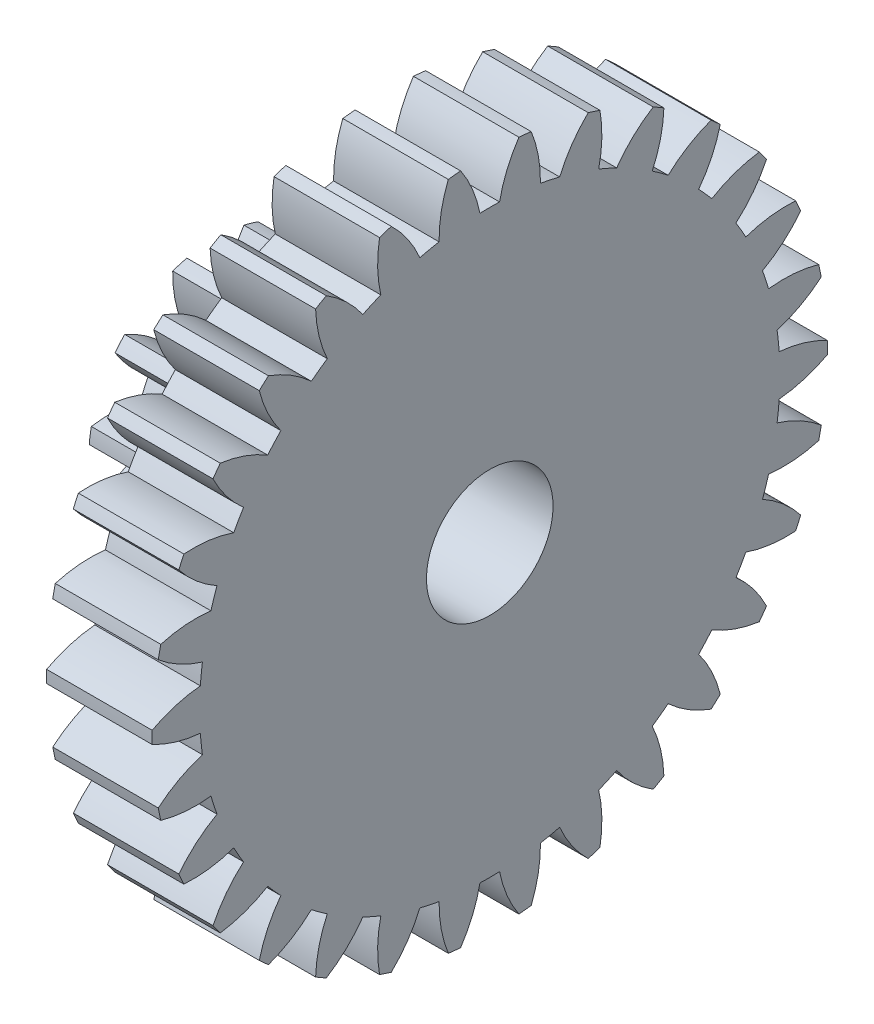
SolidWorks part; units mm, degrees
ref_plane "Plane1" through (0, 0, 0) normal (0, 0, 1) x (1, 0, 0)
ref_plane "Plane2" through (0, 0, 0) normal (0, 1, 0) x (1, 0, 0)
ref_plane "Plane3" through (0, 0, 0) normal (1, 0, 0) x (0, 0, -1)
sketch "HoldingSke" plane through (0, 0, 0) normal (0, 1, 0) x (1, 0, 0)
  line L0 (0, 0) -> (1.7321, -1)
  line L1 (-15, 0) -> (100, 0) construction
  line L2 (0, 0) -> (-2.1039, 2.3779)
  line L3 (0, 0) -> (-11.863, 4.5341)
  line L4 (0, 0) -> (7.479, 4.318)
  line L5 (0, 0) -> (-6.0902, -2.2715)
  line L6 (0, 0) -> (-2.0724, -1.3983)
  line L7 (-2.1039, 2.3779) -> (-0.7048, 8.7256)
  line L8 (-76.2, 54.61) -> (-75.7, 54.61)
  line L9 (-71.009, 38.7566) -> (-53.1078, 45.2721)
  line L10 (-76.2, 71.12) -> (104.1128, 71.12)
  line L11 (0, 0) -> (-2.5, 0)
  line L12 (-76.2, 101.6) -> (-76.181, 101.6)
  line L13 (24.9733, 27.94) -> (52.9518, 28.4284)
  line L14 (24.9733, 27.94) -> (24.9743, 27.94)
  line L15 (24.9733, 27.94) -> (100.4006, 29.5858)
  line L16 (-63.627, -0.5) -> (-12.827, -0.5)
  circle A0 centre (0, 0) radius 1.5
  circle A1 centre (0, 0) radius 3
  circle A2 centre (0, 0) radius 3
  circle A3 centre (0, 0) radius 1.5
  dimension "MHD" = 6
  dimension "Hub_dia" = 6
  dimension "Bore" = 3
  dimension "MBD" = 3
  dimension "Num_teeth" = 30
  dimension "Pitch" = 2
  dimension "Overall_len" = 6.5
  dimension "Show_teeth" = 30
  dimension "Thickness" = 2.5
  dimension "OAL" = 6.5001
  dimension "T_dim" = 0.5
  dimension "Ap" = 20
  dimension "H" = 19.05
  dimension "Pitch_radius" = 180.3128
  dimension "Width" = 2.5
  dimension "Backlash" = 0.019
  dimension "Addendum_fac" = 1
  dimension "Dedendum_fac" = 1.25
  dimension "Clearance_fac" = 0.25
  dimension "Dedendum_add" = 0.001
  dimension "Module" = 0.5
sketch "BasProSke" plane through (0, 0, 0) normal (0, 1, 0) x (1, 0, 0)
  line L0 (-10, 0) -> (60, 0) construction
  line L1 (0, 0) -> (0, 8)
  line L2 (0, 0) -> (2.5, 0)
  line L3 (2.5, 0) -> (2.5, 8)
  line L4 (2.5, 8) -> (0, 8)
  dimension "Thickness" = 2.5
  dimension "Diameter" = 16
revolve "Base-Revolve" add sketch "BasProSke" angle 360 about L0
sketch "TooCutSke" plane through (0, 0, 0) normal (1, 0, 0) x (0, 0, -1)
  line L1 (0, 0) -> (0, 107) construction
  line L2 (0, 0) -> (-0.4258, 7.4879) construction
  line L3 (0, 0) -> (-1.5661, 14.9007) construction
  line L4 (-0.4258, 7.4879) -> (-0.7831, 7.4504) construction
  arc A0 (0.2331, 6.87) -> (-0.2331, 6.87) centre (0, 0) ccw
  arc A1 (0.707, 7.9942) -> (-0.707, 7.9942) centre (0, 0) ccw
  circle A2 centre (0, 0) radius 7.5 construction
  circle A3 centre (0, 0) radius 7.0477 construction
  arc A4 (-0.2331, 6.87) -> (-0.707, 7.9942) centre (-3.1767, 6.2911) ccw
  arc A5 (0.707, 7.9942) -> (0.2331, 6.87) centre (3.1767, 6.2911) ccw
  dimension "Root_dia" = 13.748
  dimension "Overcut_dia" = 16.0508
  dimension "Pitch_dia" = 15
  dimension "Base_dia" = 14.0954
  dimension "Flank_rad" = 3
  dimension "Half_ang" = 6
  dimension "Half_CT" = 0.3593
extrude "ToothCut" cut sketch "TooCutSke" along normal through all
fillet "Breaks" [suppressed] radius 0.01
fillet "RootFillets" [suppressed] radius 0.126
pattern_circular "TeethCuts" count 30 over 360 about axis through (0, 0, 0) along (1, 0, 0) of "ToothCut", "RootFillets", "Breaks"
sketch "HubNeaOneSke" plane through (0, 0, 0) normal (-1, 0, 0) x (0, 0, 1)
  circle A0 centre (0, 0) radius 3
  dimension "Diameter" = 6
extrude "HubNearOne" add sketch "HubNeaOneSke" along normal blind 4.0001
sketch "HubNeaBotSke" plane through (0, 0, 0) normal (-1, 0, 0) x (0, 0, 1)
  circle A0 centre (0, 0) radius 3
  dimension "Diameter" = 6
extrude "HubNearBoth" [suppressed] add sketch "HubNeaBotSke" along normal blind 2
ref_plane "FarPln" through (2.5, 0, 0) normal (1, 0, 0) x (0, 0, -1)
sketch "HubFarSke" plane through (2.5, 0, 0) normal (1, 0, 0) x (0, 0, -1)
  circle A0 centre (0, 0) radius 3
  dimension "Diameter" = 6
extrude "HubFar" [suppressed] add sketch "HubFarSke" along normal blind 2
sketch "BorSke" plane through (0, 0, 0) normal (1, 0, 0) x (0, 0, -1)
  circle A0 centre (0, 0) radius 1.5
  dimension "Diameter" = 3
extrude "Bore" cut sketch "BorSke" along normal mid plane 13.0001
sketch "KeySke" plane through (0, 0, 0) normal (1, 0, 0) x (0, 0, -1)
  line L0 (-0.6, 0) -> (-0.6, 2)
  line L1 (-0.6, 2) -> (0.6, 2)
  line L2 (0.6, 2) -> (0.6, 0)
  line L3 (0, 0) -> (0, 34) construction
  line L4 (-0.6, 0) -> (0.6, 0)
  dimension "Offset" = 2
  dimension "Width" = 1.2
extrude "Keyway" [suppressed] cut sketch "KeySke" along normal mid plane 13.0001
pattern_circular "Keyway2" [suppressed] count 2 every 90 about axis through (-10, 0, 0) along (1, 0, 0)
sketch "Sketch2" plane through (-4.0001, 0, 0) normal (-1, 0, 0) x (0, 0, 1)
  line L0 (0, 1.8486) -> (0, 3) construction
  line L1 (0, 1.8486) -> (0, 0) construction
  arc A0 (0.2331, 1.8446) -> (-0.2331, 1.8446) centre (0, -5.0254) ccw
  arc A1 (0.707, 2.9688) -> (-0.707, 2.9688) centre (0, -5.0254) ccw
  arc A2 (-0.2331, 1.8446) -> (-0.707, 2.9688) centre (-3.1767, 1.2657) ccw
  circle A5 centre (0, 0) radius 3 construction
  arc A6 (0.2331, 1.8446) -> (0.707, 2.9688) centre (3.1767, 1.2657) cw
  point P8 (0, 0)
  dimension "D1" = 8.0254
  dimension "D4" = 3
  dimension "D2" = 1.1514
  dimension "D5" = 0.4662
  dimension "D6" = 0.707
extrude "Cut-Extrude1" cut sketch "Sketch2" against normal up to surface (4.0001 mm away) up to face at (0, 0, -3)
pattern_circular "CirPattern1" count 11 over 360 about axis through (0, 0, 0) along (1, 0, 0) of "Cut-Extrude1"
equation "' \"Module@HoldingSke\" = 6.35"
equation "' \"Num_teeth@HoldingSke\" = 12"
equation "' \"Ap@HoldingSke\" =  20"
equation "' \"Ap@HoldingSke\" = 20"
equation "' \"Width@HoldingSke\" = 0.5 * 25.4"
equation "' \"Hub_dia@HoldingSke\"= 1 * 25.4"
equation "' \"Hub_dia@HoldingSke\" = 1 * 25.4"
equation "' \"Overall_len@HoldingSke\" = 1.0 * 25.4"
equation "' \"Bore@HoldingSke\" = 0.75 * 25.4"
equation "' \"T_dim@HoldingSke\" = 0.1 * 25.4"
equation "' \"Width@KeySke\" = 0.25 * 25.4"
equation "' \"Show_teeth@HoldingSke\" = 13"
equation "' \"Backlash@HoldingSke\" = 0.009 * 25.4"
equation "' \"Addendum_fac@HoldingSke\" = 1.0"
equation "' \"Dedendum_fac@HoldingSke\" = 1.25"
equation "' \"Dedendum_add@HoldingSke\" = 0.00005 * 25.4"
equation "' \"Clearance_fac@HoldingSke\" = 0.25"
equation "\"Pitch@HoldingSke\" = 1 / \"Module@HoldingSke\""
equation "\"Overcut_dia@TooCutSke\" = (\"Num_teeth@HoldingSke\" + 2 * \"Addendum_fac@HoldingSke\") / \"Pitch@HoldingSke\" + 0.002 * 25.4"
equation "\"Pitch_dia@TooCutSke\" = \"Num_teeth@HoldingSke\" / \"Pitch@HoldingSke\""
equation "\"Base_dia@TooCutSke\" = \"Num_teeth@HoldingSke\" / \"Pitch@HoldingSke\" * cos((\"Ap@HoldingSke\"  * 3.14159265 / 180))"
equation "\"Root_dia@TooCutSke\" = (\"Num_teeth@HoldingSke\" + 2) / \"Pitch@HoldingSke\" - 2 * (\"Addendum_fac@HoldingSke\" + \"Dedendum_fac@HoldingSke\") / \"Pitch@HoldingSke\" - \"Dedendum_add@HoldingSke\" * 2"
equation "\"Half_ang@TooCutSke\" = 180 / \"Num_teeth@HoldingSke\""
equation "\"Half_CT@TooCutSke\" = \"Num_teeth@HoldingSke\" / \"Pitch@HoldingSke\" * sin((3.14159265 / 2 / \"Num_teeth@HoldingSke\")) / 2 - 7 * \"Backlash@HoldingSke\" / 4"
equation "\"Flank_rad@TooCutSke\" = \"Num_teeth@HoldingSke\" / \"Pitch@HoldingSke\" / 5"
equation "\"Radius@RootFillets\" = \"Clearance_fac@HoldingSke\" / \"Pitch@HoldingSke\" + \"Dedendum_add@HoldingSke\""
equation "\"Break_rad@Breaks\" = 0.02 / \"Pitch@HoldingSke\""
equation "\"Thickness@HoldingSke\" = \"Width@HoldingSke\""
equation "\"OAL@HoldingSke\" = \"Thickness@HoldingSke\""
equation "\"MHD@HoldingSke\" = (\"Num_teeth@HoldingSke\" + 2) / \"Pitch@HoldingSke\" - 2 * (\"Addendum_fac@HoldingSke\" + \"Dedendum_fac@HoldingSke\")  / \"Pitch@HoldingSke\" - \"Dedendum_add@HoldingSke\" * 2"
equation "\"MBD@HoldingSke\" = (\"Num_teeth@HoldingSke\" + 2) / \"Pitch@HoldingSke\" - 2 * (\"Addendum_fac@HoldingSke\" + \"Dedendum_fac@HoldingSke\")  / \"Pitch@HoldingSke\" - \"Dedendum_add@HoldingSke\" * 2 - 0.002 * 25.4"
equation "\"MHD@HoldingSke\" = ((sgn( \"MHD@HoldingSke\" - \"Hub_dia@HoldingSke\" )-1)*( \"MHD@HoldingSke\" - \"Hub_dia@HoldingSke\" ))/-2+ \"Hub_dia@HoldingSke\""
equation "\"MBD@HoldingSke\" = ((sgn( \"MBD@HoldingSke\" - \"Bore@HoldingSke\" )-1)*( \"MBD@HoldingSke\" - \"Bore@HoldingSke\" ))/-2+ \"Bore@HoldingSke\""
equation "\"OAL@HoldingSke\" = ((sgn( \"OAL@HoldingSke\" - \"Overall_len@HoldingSke\" )+1)*( \"OAL@HoldingSke\" - \"Overall_len@HoldingSke\" ))/2 + \"Overall_len@HoldingSke\" + 0.000002 * 25.4"
equation "\"Num_teeth@TeethCuts\" = int( \"Show_teeth@HoldingSke\" ) + 1"
equation "\"Num_teeth@TeethCuts\" = ((sgn( \"Num_teeth@TeethCuts\" - \"Num_teeth@HoldingSke\" )-1)*( \"Num_teeth@TeethCuts\" - \"Num_teeth@HoldingSke\" ))/-2+ \"Num_teeth@HoldingSke\""
equation "\"Num_teeth@TeethCuts\" = ((sgn( \"Num_teeth@TeethCuts\" - 2.0)+1)*( \"Num_teeth@TeethCuts\" - 2.0))/2 +2.0"
equation "\"Angle@TeethCuts\" = 360.0 / \"Num_teeth@HoldingSke\""
equation "\"Diameter@BasProSke\" = (\"Num_teeth@HoldingSke\" + 2 * \"Addendum_fac@HoldingSke\") / \"Pitch@HoldingSke\""
equation "\"Thickness@BasProSke\"  = \"Thickness@HoldingSke\""
equation "' \"Fillet_rad@BasProSke\" =  \"Thickness@HoldingSke\" * 0.05"
equation "' \"Fillet_rad@BasProSke\" = \"Thickness@HoldingSke\" * 0.05"
equation "\"MHD@HoldingSke\" = ((sgn( \"MHD@HoldingSke\" - \"Root_dia@TooCutSke\" )-1)*( \"MHD@HoldingSke\" - \"Root_dia@TooCutSke\" ))/-2+ \"Root_dia@TooCutSke\""
equation "\"Diameter@HubNeaOneSke\" = \"MHD@HoldingSke\""
equation "\"Length@HubNearOne\" = \"OAL@HoldingSke\" - \"Thickness@BasProSke\""
equation "\"Diameter@HubNeaBotSke\" = \"MHD@HoldingSke\""
equation "\"Length@HubNearBoth\" = ( \"OAL@HoldingSke\" - \"Thickness@BasProSke\" ) / 2.0"
equation "\"Thickness@FarPln\" = \"Thickness@BasProSke\""
equation "\"Diameter@HubFarSke\" = \"MHD@HoldingSke\""
equation "\"Length@HubFar\" = ( \"OAL@HoldingSke\" - \"Thickness@BasProSke\" ) / 2.0"
equation "\"Diameter@BorSke\" = \"MBD@HoldingSke\""
equation "\"D1@Bore\" = \"OAL@HoldingSke\" * 2.0"
equation "\"D1@Keyway\" = \"OAL@HoldingSke\" * 2.0"
equation "\"Offset@KeySke\" = \"T_dim@HoldingSke\" + \"MBD@HoldingSke\" / 2.0"
